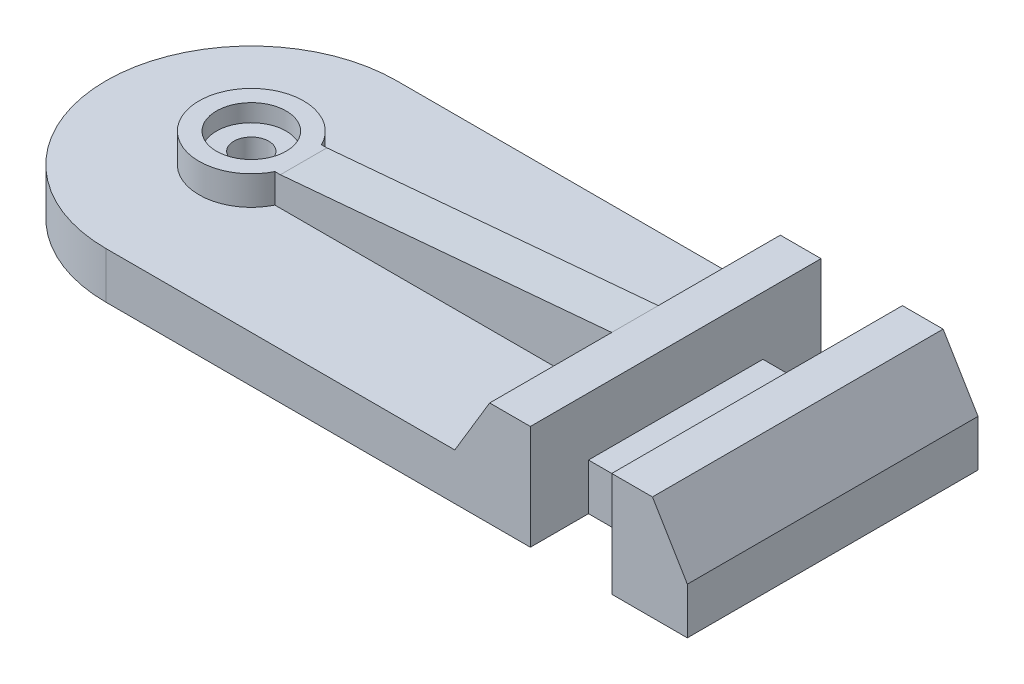
SolidWorks part; units mm, degrees
material "ABS"
ref_plane "前视基准面" through (0, 0, 0) normal (0, 0, 1) x (1, 0, 0)
ref_plane "上视基准面" through (0, 0, 0) normal (0, 1, 0) x (1, 0, 0)
ref_plane "右视基准面" through (0, 0, 0) normal (1, 0, 0) x (0, 0, -1)
sketch "草图1" plane through (0, 0, 0) normal (0, 1, 0) x (1, 0, 0)
  line L0 (0, 12.5) -> (50, 12.5)
  line L1 (50, 12.5) -> (50, -12.5)
  line L2 (50, -12.5) -> (0, -12.5)
  line L3 (-17.9664, 0) -> (77.456, 0) construction
  circle A0 centre (0, 0) radius 12.5
  circle A1 centre (0, 0) radius 1.5
  circle A2 centre (40, 0) radius 1.5
  dimension "D1" = 25
  dimension "D3" = 3
  dimension "D4" = 3
  dimension "D2" = 50
  dimension "D5" = 40
extrude "凸台-拉伸1" add sketch "草图1" along normal blind 4 contours A0 L3 A1 | L3 A0 A1 | A0 L3 A2 L1 L0 | L3 A0 L2 L1 A2
sketch "草图2" plane through (0, 4, 0) normal (0, 1, 0) x (1, 0, 0)
  circle A0 centre (0, 0) radius 3
  circle A1 centre (0, 0) radius 4.5
  dimension "D1" = 6
  dimension "D2" = 9
extrude "凸台-拉伸2" add sketch "草图2" along normal blind 2.5
sketch "草图3" plane through (0, 0, 12.5) normal (0, 0, 1) x (1, 0, 0)
  line L0 (40, 13.5103) -> (40, -9.5748) construction
  line L1 (33, 9) -> (47, 9)
  line L2 (47, 9) -> (50, 4)
  line L3 (50, 4) -> (30, 4)
  line L4 (50, 4) -> (0, 4) construction
  line L5 (33, 9) -> (30, 4)
  point P11 (40, 4)
  point P12 (40, 9)
  dimension "D1" = 40
  dimension "D2" = 7
  dimension "D3" = 5
extrude "凸台-拉伸3" add sketch "草图3" against normal up to surface (25 mm away) up to face at (25, 2, -12.5)
sketch "草图4" plane through (0, 0, 12.5) normal (0, 0, 1) x (1, 0, 0)
  line L0 (40, 14.712) -> (40, -12.897) construction
  line L1 (36.5, 9) -> (43.5, 9)
  line L2 (47, 9) -> (33, 9) construction
  line L3 (43.5, 9) -> (43.5, 4)
  line L4 (43.5, 4) -> (36.5, 4)
  line L5 (36.5, 9) -> (36.5, 4)
  point P10 (40, 4)
  point P11 (40, 9)
  dimension "D1" = 40
  dimension "D2" = 3.5
  dimension "D3" = 5
extrude "切除-拉伸1" cut sketch "草图4" against normal through all
sketch "草图5" plane through (0, 4, 0) normal (0, 1, 0) x (1, 0, 0)
  line L0 (-19.9448, 0) -> (64.5272, 0) construction
  line L1 (36.5, -12.5) -> (43.5, -12.5)
  line L2 (43.5, -12.5) -> (43.5, -7.5)
  line L3 (43.5, 12.5) -> (43.5, -12.5) construction
  line L4 (43.5, -7.5) -> (36.5, -7.5)
  line L5 (36.5, 12.5) -> (36.5, -12.5) construction
  line L6 (36.5, -7.5) -> (36.5, -12.5)
  line L7 (36.5, 7.5) -> (36.5, 12.5)
  line L8 (36.5, 12.5) -> (43.5, 12.5)
  line L9 (43.5, 12.5) -> (43.5, 7.5)
  line L10 (43.5, 7.5) -> (36.5, 7.5)
  dimension "D1" = 5
extrude "切除-拉伸2" cut sketch "草图5" against normal through all
sketch "草图6" plane through (0, 0, 0) normal (0, 0, 1) x (1, 0, 0)
  line L0 (30, 4) -> (33, 9)
  line L1 (33, 9) -> (4.5, 6.5)
  line L2 (4.5, 6.5) -> (-4.5, 6.5) construction
  line L3 (4.5, 4) -> (4.5, 6.5) construction
  line L4 (4.5, 6.5) -> (3.2158, 6.5)
  line L5 (3.2158, 6.5) -> (3.2158, 4)
  line L6 (30, 4) -> (0, 4) construction
  line L7 (3.2158, 4) -> (30, 4)
extrude "凸台-拉伸4" add sketch "草图6" along normal mid plane 4
sketch "草图7" plane through (0, 4, 0) normal (0, 1, 0) x (1, 0, 0)
  circle A0 centre (0, 0) radius 3
  circle A1 centre (0, 0) radius 1.5
extrude "凸台-拉伸5" add sketch "草图7" along normal blind 1
